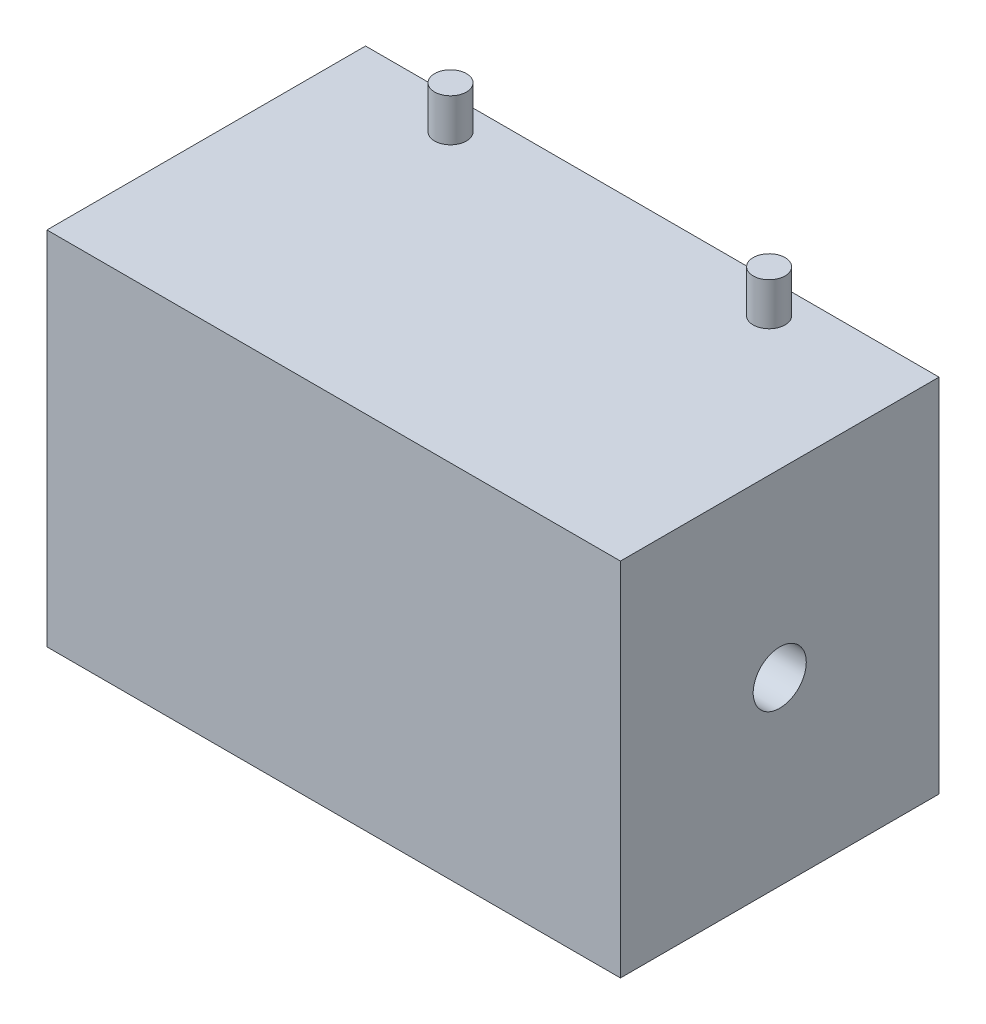
SolidWorks part; units mm, degrees
ref_plane "Front Plane" through (0, 0, 0) normal (0, 0, 1) x (1, 0, 0)
ref_plane "Top Plane" through (0, 0, 0) normal (0, 1, 0) x (1, 0, 0)
ref_plane "Right Plane" through (0, 0, 0) normal (1, 0, 0) x (0, 0, -1)
sketch "Sketch1" plane through (0, 0, 0) normal (0, 0, 1) x (1, 0, 0)
  line L1 (0, 0) -> (270, 0)
  line L2 (0, 0) -> (0, 170)
  line L3 (0, 170) -> (270, 170)
  line L4 (270, 0) -> (270, 170)
  dimension "D1" = 270
  dimension "D2" = 170
extrude "Boss-Extrude1" add sketch "Sketch1" along normal blind 150
sketch "Sketch2" plane through (270, 0, 0) normal (1, 0, 0) x (0, 0, -1)
  line L0 (0, 0) -> (0, 170) construction
  line L2 (-150, 0) -> (0, 0) construction
  circle A0 centre (-75, 85) radius 12.5
  point P4 (0, 0)
  point P7 (0, 0)
  point P8 (0, 0)
  dimension "D1" = 25
  dimension "D2" = 75
  dimension "D3" = 85
extrude "Cut-Extrude1" cut sketch "Sketch2" against normal blind 200 contours A0
sketch "Sketch3" plane through (0, 0, 0) normal (0, -1, 0) x (1, 0, 0)
  line L0 (0, 15) -> (270, 15) construction
  line L1 (0, 150) -> (0, 0) construction
  line L2 (270, 150) -> (270, 0) construction
  line L3 (205, 150) -> (205, 0) construction
  line L4 (0, 150) -> (270, 150) construction
  line L5 (0, 0) -> (270, 0) construction
  line L6 (55, 150) -> (55, 0) construction
  circle A0 centre (55, 15) radius 7.5
  circle A1 centre (205, 15) radius 7.5
  point P19 (205, 15)
  dimension "D4" = 15
  dimension "D5" = 15
  dimension "D1" = 15
  dimension "D2" = 65
  dimension "D3" = 150
extrude "Boss-Extrude2" add sketch "Sketch3" along normal blind 20 and the other way blind 190
